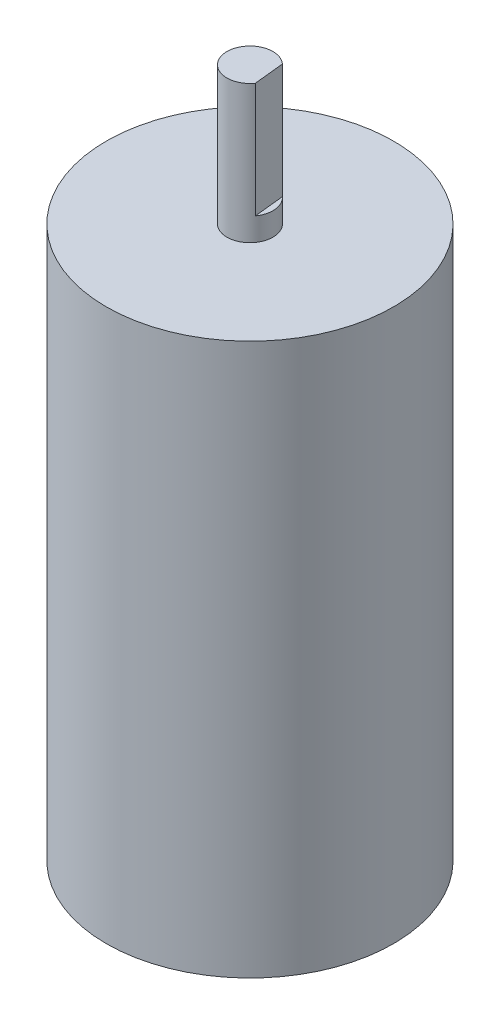
SolidWorks part; units mm, degrees
ref_plane "前视基准面" through (0, 0, 0) normal (0, 0, 1) x (1, 0, 0)
ref_plane "上视基准面" through (0, 0, 0) normal (0, 1, 0) x (1, 0, 0)
ref_plane "右视基准面" through (0, 0, 0) normal (1, 0, 0) x (0, 0, -1)
sketch "草图1" plane through (0, 0, 0) normal (0, 1, 0) x (1, 0, 0)
  circle A0 centre (0, 0) radius 12.5
  dimension "D1" = 25
extrude "凸台-拉伸1" add sketch "草图1" along normal blind 48
sketch "草图2" plane through (0, 48, 0) normal (0, 1, 0) x (1, 0, 0)
  circle A0 centre (0, 0) radius 2
  dimension "D1" = 4
extrude "凸台-拉伸2" add sketch "草图2" along normal blind 12
sketch "草图3" plane through (0, 60, 0) normal (0, 1, 0) x (1, 0, 0)
  line L0 (1.629, -1.1603) -> (1.3549, 1.4712)
  circle A1 centre (0, 0) radius 2
  arc A2 (1.629, -1.1603) -> (1.3549, 1.4712) centre (0, 0) ccw
  dimension "D2" = 1.5
  dimension "D1" = 0
extrude "切除-拉伸1" cut sketch "草图3" against normal blind 10
